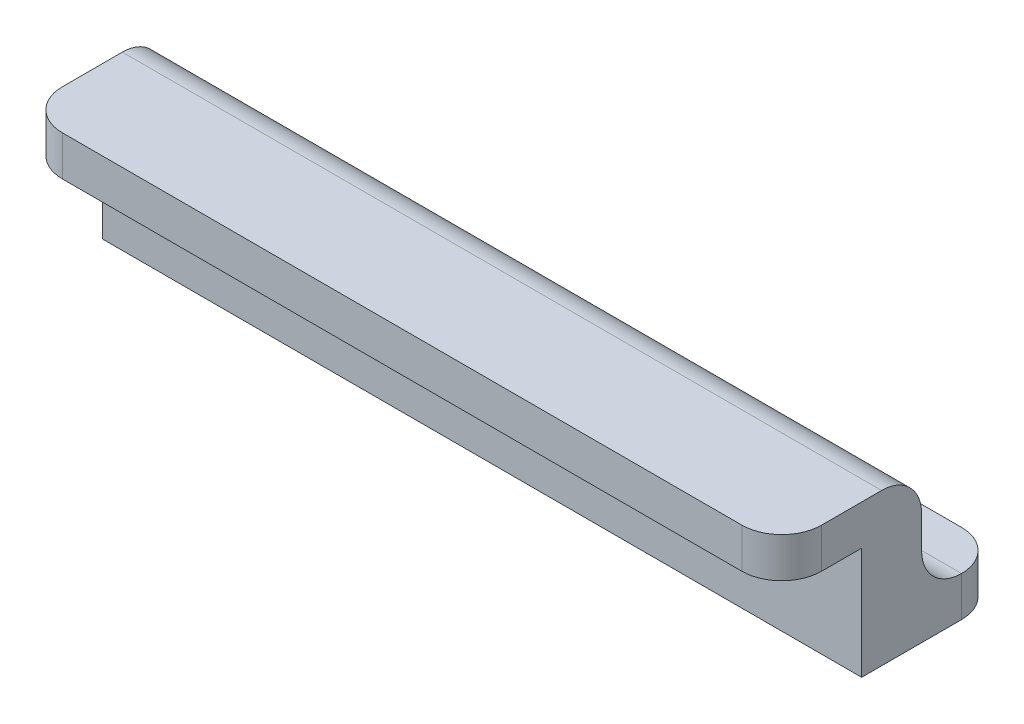
SolidWorks part; units mm, degrees
ref_plane "Front Plane" through (0, 0, 0) normal (0, 0, 1) x (1, 0, 0)
ref_plane "Top Plane" through (0, 0, 0) normal (0, 1, 0) x (1, 0, 0)
ref_plane "Right Plane" through (0, 0, 0) normal (1, 0, 0) x (0, 0, -1)
sketch "Sketch1" plane through (0, 0, 0) normal (0, 1, 0) x (1, 0, 0)
  line L1 (2, 0) -> (36, 0)
  line L2 (0, 2) -> (0, 6)
  line L3 (1, 7) -> (37, 7)
  line L4 (38, 2) -> (38, 6)
  arc A0 (37, 7) -> (38, 6) centre (37, 6) cw
  arc A1 (36, 0) -> (38, 2) centre (36, 2) ccw
  arc A2 (2, 0) -> (0, 2) centre (2, 2) cw
  arc A3 (0, 6) -> (1, 7) centre (1, 6) cw
  point P11 (0, 0)
  dimension "D1" = 1
  dimension "D2" = 2
  dimension "D3" = 38
  dimension "D4" = 7
extrude "Boss-Extrude1" add sketch "Sketch1" along normal blind 2
sketch "Sketch2" plane through (0, 2, 0) normal (0, 1, 0) x (1, 0, 0)
  line L0 (19, 0) -> (19, 10.7795) construction
  line L1 (2, 0) -> (36, 0) construction
  line L2 (38, 6) -> (38, 2)
  line L4 (0, 6) -> (0, 2) construction
  line L5 (37, 7) -> (1, 7) construction
  line L13 (0, 6) -> (0, 2)
  line L14 (37, 7) -> (1, 7)
  line L21 (37.2, 5.3) -> (37.2, 0.4)
  line L22 (1.3, 5.8) -> (36.7, 5.8)
  line L23 (0.8, 0.4) -> (0.8, 5.3)
  arc A0 (38, 2) -> (37.2, 0.4) centre (36, 2) cw
  arc A1 (37, 7) -> (38, 6) centre (37, 6) cw
  arc A3 (1, 7) -> (0, 6) centre (1, 6) ccw construction
  arc A4 (0, 2) -> (2, 0) centre (2, 2) ccw construction
  arc A11 (1, 7) -> (0, 6) centre (1, 6) ccw
  arc A12 (0, 2) -> (0.8, 0.4) centre (2, 2) ccw
  arc A15 (37.2, 5.3) -> (36.7, 5.8) centre (36.7, 5.3) ccw
  arc A16 (1.3, 5.8) -> (0.8, 5.3) centre (1.3, 5.3) ccw
  point P10 (38, 4)
  point P14 (19, 4.9)
  point P32 (19, 7)
  dimension "D2" = 1.2
  dimension "D3" = 0.5
  dimension "D1" = 0.8
extrude "Boss-Extrude2" add sketch "Sketch2" against normal blind 7.6
sketch "Sketch4" plane through (0, -5.6, 0) normal (0, -1, 0) x (1, 0, 0)
  line L5 (37, -7) -> (1, -7) construction
  line L8 (37, -7) -> (1, -7)
  line L9 (0, -6) -> (0, -9)
  line L10 (2, -11) -> (36, -11)
  line L11 (38, -9) -> (38, -6)
  arc A9 (37, -7) -> (38, -6) centre (37, -6) ccw construction
  arc A10 (0, -6) -> (1, -7) centre (1, -6) ccw construction
  arc A11 (37, -7) -> (38, -6) centre (37, -6) ccw
  arc A12 (0, -6) -> (1, -7) centre (1, -6) ccw
  arc A13 (0, -9) -> (2, -11) centre (2, -9) ccw
  arc A14 (36, -11) -> (38, -9) centre (36, -9) ccw
  dimension "D1" = 2
  dimension "D2" = 4
extrude "Boss-Extrude3" add sketch "Sketch4" against normal blind 2
sketch "Sketch5" plane through (0, 0, 0) normal (0, -1, 0) x (1, 0, 0)
  line L0 (38, -2) -> (38, -9) construction
  line L1 (38, -5.8) -> (0, -5.8)
  line L2 (38, -5.8) -> (38, 0)
  line L3 (38, 0) -> (0, 0)
  line L4 (0, -5.8) -> (0, 0)
  line L5 (2, 0) -> (36, 0) construction
  line L6 (1.3, -5.8) -> (36.7, -5.8) construction
  line L7 (0, -9) -> (0, -2) construction
extrude "Cut-Extrude1" cut sketch "Sketch5" along normal through all
sketch "Sketch6" plane through (0, -5.6, 0) normal (0, -1, 0) x (1, 0, 0)
  line L0 (38, -5.8) -> (38, -2) construction
  line L1 (38, -7) -> (0, -7)
  line L2 (38, -7) -> (38, -4)
  line L3 (38, -4) -> (0, -4)
  line L4 (0, -7) -> (0, -4)
  line L5 (37, -7) -> (1, -7) construction
  line L6 (0, -2) -> (0, -5.8) construction
  dimension "D1" = 3
extrude "Boss-Extrude4" add sketch "Sketch6" against normal up to surface (7.6 mm away) up to face at (19, 2, -3.6982)
fillet "Fillet1" radius 2 2 edges at (19, 2, -7) (19, -3.6, -7)
